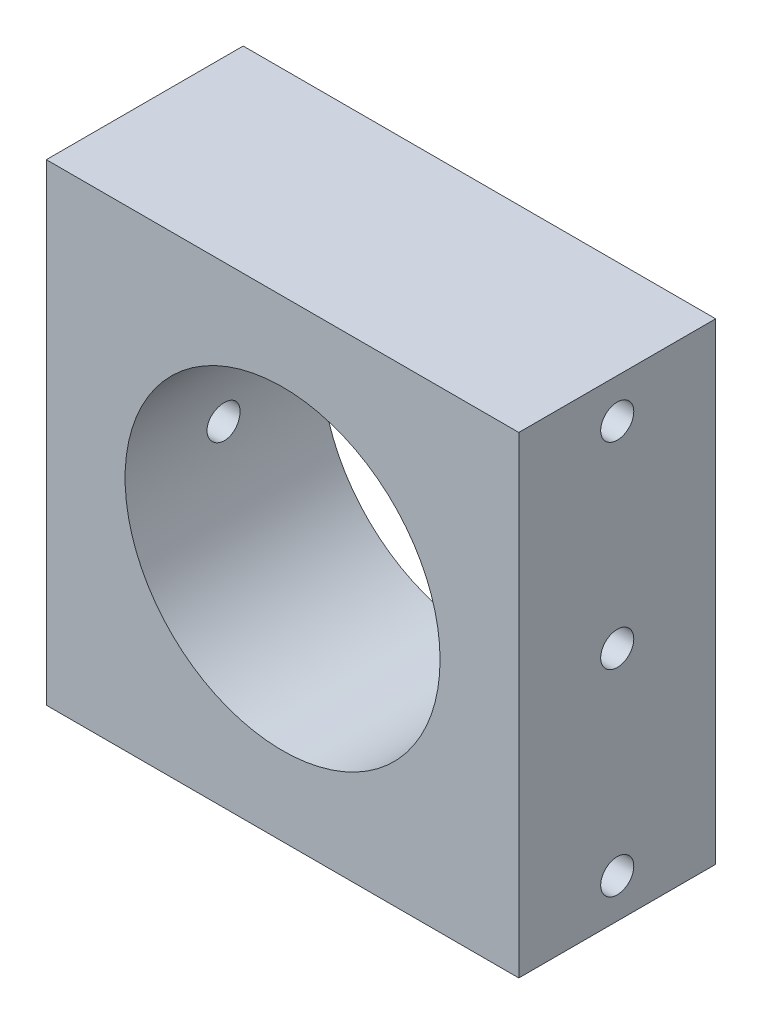
SolidWorks part; units mm, degrees
ref_plane "Front Plane" through (0, 0, 0) normal (0, 0, 1) x (1, 0, 0)
ref_plane "Top Plane" through (0, 0, 0) normal (0, 1, 0) x (1, 0, 0)
ref_plane "Right Plane" through (0, 0, 0) normal (1, 0, 0) x (0, 0, -1)
sketch "Sketch1" plane through (0, 0, 0) normal (0, 0, 1) x (1, 0, 0)
  line L0 (0, 0) -> (0, 191362.0965) construction
  line L1 (0, 0) -> (191362.0965, 0) construction
  line L2 (-20, 0) -> (-30, 0)
  line L3 (-30, -30) -> (-30, 30)
  line L4 (-30, 30) -> (30, 30)
  line L5 (20, 0) -> (30, 0)
  line L6 (30, -30) -> (30, 30)
  line L7 (-30, -30) -> (30, -30)
  circle A0 centre (0, 0) radius 20
  point P13 (0, 30)
  dimension "D1" = 20
  dimension "D2" = 60
  dimension "D3" = 30
extrude "Boss-Extrude1" add sketch "Sketch1" along normal blind 25 contours A0 L5 L6 L4 L3 L2 | A0 L2 L3 L7 L6 L5
sketch "Sketch2" plane through (30, 0, 0) normal (1, 0, 0) x (0, 0, -1)
  line L0 (-12.5, 30) -> (-12.5, -30) construction
  line L1 (-25, 30) -> (0, 30) construction
  line L3 (-25, 30) -> (0, 30) construction
  line L4 (-25, -30) -> (0, -30) construction
  line L5 (0, 0) -> (-25, 0) construction
  line L6 (-25, -30) -> (-25, 30) construction
  circle A0 centre (-12.5, 25) radius 2.1
  circle A1 centre (-12.5, -25) radius 2.1
  circle A2 centre (-12.5, 0) radius 2.1
  dimension "D1" = 4.2
  dimension "D2" = 5
  dimension "D3" = 5
extrude "Cut-Extrude1" cut sketch "Sketch2" against normal through all
fillet "Fillet1" [suppressed] radius 20
